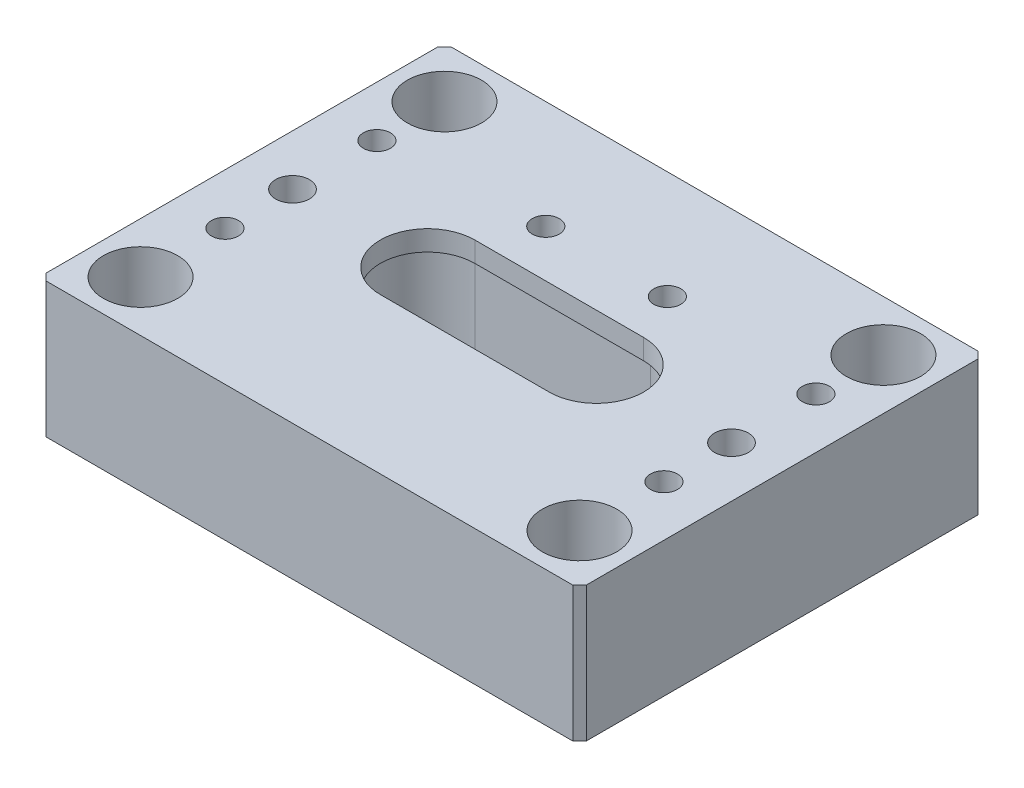
SolidWorks part; units mm, degrees
ref_plane "Front Plane" through (0, 0, 0) normal (0, 0, 1) x (1, 0, 0)
ref_plane "Bottom Plane" through (0, 0, 0) normal (0, 1, 0) x (1, 0, 0)
ref_plane "Right Plane" through (0, 0, 0) normal (1, 0, 0) x (0, 0, -1)
sketch "Sketch1" plane through (0, 0, 0) normal (0, 1, 0) x (1, 0, 0)
  line L0 (39, 30) -> (40, 29)
  line L5 (-39, 30) -> (39, 30)
  line L6 (-40, 29) -> (-40, -29)
  line L11 (-39, -30) -> (39, -30)
  line L12 (40, 29) -> (40, -29)
  line L13 (-40, 30) -> (40, -30) construction
  line L14 (-40, -30) -> (40, 30) construction
  line L23 (39, -30) -> (40, -29)
  line L24 (-40, 29) -> (-39, 30)
  line L25 (-40, -29) -> (-39, -30)
extrude "Boss-Extrude1" add sketch "Sketch1" along normal blind 20 contours L6 L25 L11 L23 L12 L0 L5 L24
sketch "Sketch2" plane through (0, 20, 0) normal (0, 1, 0) x (1, 0, 0)
  line L5 (-12.5, 7) -> (12.5, 7)
  line L7 (-12.5, -7) -> (12.5, -7)
  line L9 (-12.5, 7) -> (12.5, -7) construction
  line L10 (-12.5, -7) -> (12.5, 7) construction
  line L11 (-39, 30) -> (39, 30) construction
  arc A0 (-12.5, 7) -> (-12.5, -7) centre (-12.5, 0) ccw
  arc A1 (12.5, -7) -> (12.5, 7) centre (12.5, 0) ccw
  point P0 (0, 0)
  point P8 (0, 0)
  point P9 (12.5, 0)
  point P10 (0, 0)
  point P11 (0, 0)
  point P12 (0, 0)
  point P13 (0, 0)
  point P14 (0, 0)
  point P15 (0, 0)
  point P16 (0, 0)
  point P17 (0, 0)
  point P20 (0, 30)
extrude "Cut-Extrude1" cut sketch "Sketch2" against normal blind 3
ref_plane "Plane1" through (0, 0, 0) normal (0, -1, 0) x (-1, 0, 0)
sketch "Sketch3" plane through (0, 0, 0) normal (0, -1, 0) x (-1, 0, 0)
  line L1 (13, -7.5) -> (-13, -7.5)
  line L3 (13, 7.5) -> (-13, 7.5)
  line L5 (13, -7.5) -> (-13, 7.5) construction
  line L6 (13, 7.5) -> (-13, -7.5) construction
  arc A4 (-13, 7.5) -> (-13, -7.5) centre (-13, 0) ccw
  arc A7 (13, -7.5) -> (13, 7.5) centre (13, 0) ccw
  point P0 (0, 0)
  point P5 (-75.6419, 22.0706)
  point P7 (0, 0)
  point P9 (-78.2479, 18.0495)
  point P10 (0, 0)
  point P11 (0, 0)
  point P12 (0, 0)
  dimension "D2" = 7.5
  dimension "D1" = 7.5
extrude "Cut-Extrude3" cut sketch "Sketch3" against normal blind 17
ref_plane "Top Plane" through (0, 20, 0) normal (0, 1, 0) x (1, 0, 0)
sketch "Sketch4" plane through (0, 20, 0) normal (0, 1, 0) x (1, 0, 0)
  line L0 (40, 29) -> (40, -29) construction
  line L1 (-39, -30) -> (39, -30) construction
  line L2 (-40, 29) -> (-40, -29) construction
  line L3 (-39, 30) -> (39, 30) construction
  circle A0 centre (32.5, -22.5) radius 5.5
  circle A1 centre (-32.5, -22.5) radius 5.5
  circle A3 centre (-32.5, 22.5) radius 5.5
  circle A4 centre (32.5, 22.5) radius 5.5
  dimension "D1" = 2
  dimension "D5" = 7.5
  dimension "D2" = 7.5
  dimension "D3" = 7.5
  dimension "D4" = 7.5
  dimension "D6" = 7.5
sketch "Sketch5" plane through (0, 0, 0) normal (0, -1, 0) x (-1, 0, 0)
  line L0 (40, 29) -> (40, -29) construction
  line L1 (39, -30) -> (-39, -30) construction
  line L2 (-40, 29) -> (-40, -29) construction
  line L3 (39, 30) -> (-39, 30) construction
  circle A0 centre (32.5, -22.5) radius 3.3
  circle A1 centre (-32.5, -22.5) radius 3.3
  circle A2 centre (-32.5, 22.5) radius 3.3
  circle A3 centre (32.5, 22.5) radius 3.3
  dimension "D1" = 7.5
  dimension "D2" = 7.5
  dimension "D3" = 7.5
  dimension "D4" = 7.5
  dimension "D5" = 7.5
  dimension "D6" = 7.5
  dimension "D7" = 7.5
  dimension "D8" = 7.5
sketch "Sketch6" plane through (0, 20, 0) normal (0, 1, 0) x (1, 0, 0)
  line L0 (-40, 29) -> (-40, -29) construction
  line L1 (-39, -30) -> (39, -30) construction
  circle A0 centre (-9, 14) radius 2
  circle A1 centre (9, 14) radius 2
  dimension "D1" = 31
  dimension "D2" = 44
  dimension "D3" = 2
sketch "Sketch7" plane through (0, 20, 0) normal (0, 1, 0) x (1, 0, 0)
  line L0 (-39, -30) -> (39, -30) construction
  line L1 (-40, 29) -> (-40, -29) construction
  circle A0 centre (-32.5, -10) radius 2
  circle A1 centre (-32.5, 12.5) radius 2
  circle A2 centre (32.5, 12.5) radius 2
  circle A3 centre (32.5, -10) radius 2
  dimension "D1" = 20
  dimension "D2" = 7.5
  dimension "D3" = 2
  dimension "D4" = 2
  dimension "D5" = 2
sketch "Sketch8" plane through (0, 20, 0) normal (0, 1, 0) x (1, 0, 0)
  line L0 (-39, 30) -> (39, 30) construction
  line L1 (40, 29) -> (40, -29) construction
  circle A0 centre (32.5, 0) radius 2
  circle A1 centre (-32.5, 0) radius 2
  dimension "D1" = 30
  dimension "D2" = 7.5
  dimension "D3" = 2
hole_wizard "Ø4.0mm Dowel Hole1" positions "Sketch11" profile "Sketch12" hole size "Ø4.0" standard "ANSI Metric"
sketch "Sketch11" plane through (0, 20, 0) normal (0, 1, 0) x (1, 0, 0)
  point P0 (9, 14)
  point P3 (-9, 14)
sketch "Sketch12" plane through (9, 20, -14) normal (1, 0, 0) x (0, 0, 1)
  line L0 (0, 0) -> (0, 11.2017)
  line L1 (0, 11.2017) -> (2, 10)
  line L2 (2, 10) -> (2, 0)
  line L5 (2, 0) -> (0, 0)
  line L10 (0, 11.2017) -> (-2, 10) construction
  line L11 (0, -6.35) -> (0, 107.95) construction
  dimension "Hole Dia." = 4
  dimension "Hole Depth" = 10
  dimension "Drill Angle" = 118
hole_wizard "M6x1.0 Tapped Hole1" positions "Sketch13" profile "Sketch14" tap size "M6x1.0" standard "ANSI Metric" end condition through all
sketch "Sketch13" plane through (0, 20, 0) normal (0, 1, 0) x (1, 0, 0)
  point P0 (-32.5, 0)
  point P3 (32.5, 0)
sketch "Sketch14" plane through (-32.5, 20, 0) normal (1, 0, 0) x (0, 0, 1)
  line L0 (0, 0) -> (0, 20)
  line L1 (0, 20) -> (2.5, 20)
  line L2 (2.5, 20) -> (2.5, 0)
  line L5 (2.5, 0) -> (0, 0)
  line L11 (0, -6.35) -> (0, 107.95) construction
  dimension "Thru Tap Drill Dia." = 5
  dimension "Thru Tap Drill Depth" = 20
cosmetic thread "Hole Thread1" parameters "D2"=6
cosmetic thread "Hole Thread2" parameters "D2"=6
hole_wizard "CBORE for M5 Hex Head Machine Screw1" positions "Sketch15" profile "Sketch16" counterbore size "M5" standard "ANSI Metric"
sketch "Sketch15" plane through (0, 20, 0) normal (0, 1, 0) x (1, 0, 0)
  point P0 (-32.5, -22.5)
  point P3 (-32.5, 22.5)
  point P6 (32.5, 22.5)
  point P9 (32.5, -22.5)
sketch "Sketch16" plane through (-32.5, 20, 22.5) normal (1, 0, 0) x (0, 0, 1)
  line L0 (0, 0) -> (0, 20)
  line L1 (0, 20) -> (3.3, 20)
  line L2 (3.3, 20) -> (3.3, 10)
  line L3 (3.3, 10) -> (5.5, 10)
  line L4 (5.5, 10) -> (5.5, 0)
  line L5 (5.5, 0) -> (0, 0)
  line L10 (0, 20) -> (-3.3, 20) construction
  line L11 (0, -6.35) -> (0, 107.95) construction
  dimension "Hole Dia." = 6.6
  dimension "Hole Depth" = 20
  dimension "C'Bore Dia." = 11
  dimension "C'Bore Depth" = 10
  dimension "Drill Angle" = 180
hole_wizard "Ø4.0mm Dowel Hole2" positions "Sketch17" profile "Sketch18" hole size "Ø4.0" standard "ANSI Metric" end condition through all
sketch "Sketch17" plane through (0, 20, 0) normal (0, 1, 0) x (1, 0, 0)
  point P0 (32.5, 12.5)
  point P3 (32.5, -10)
  point P6 (-32.5, -10)
  point P9 (-32.5, 12.5)
sketch "Sketch18" plane through (32.5, 20, -12.5) normal (1, 0, 0) x (0, 0, 1)
  line L0 (0, 0) -> (0, 20)
  line L1 (0, 20) -> (2, 20)
  line L2 (2, 20) -> (2, 0)
  line L5 (2, 0) -> (0, 0)
  line L11 (0, -6.35) -> (0, 107.95) construction
  dimension "Thru Hole Dia." = 4
  dimension "Thru Hole Depth" = 20
